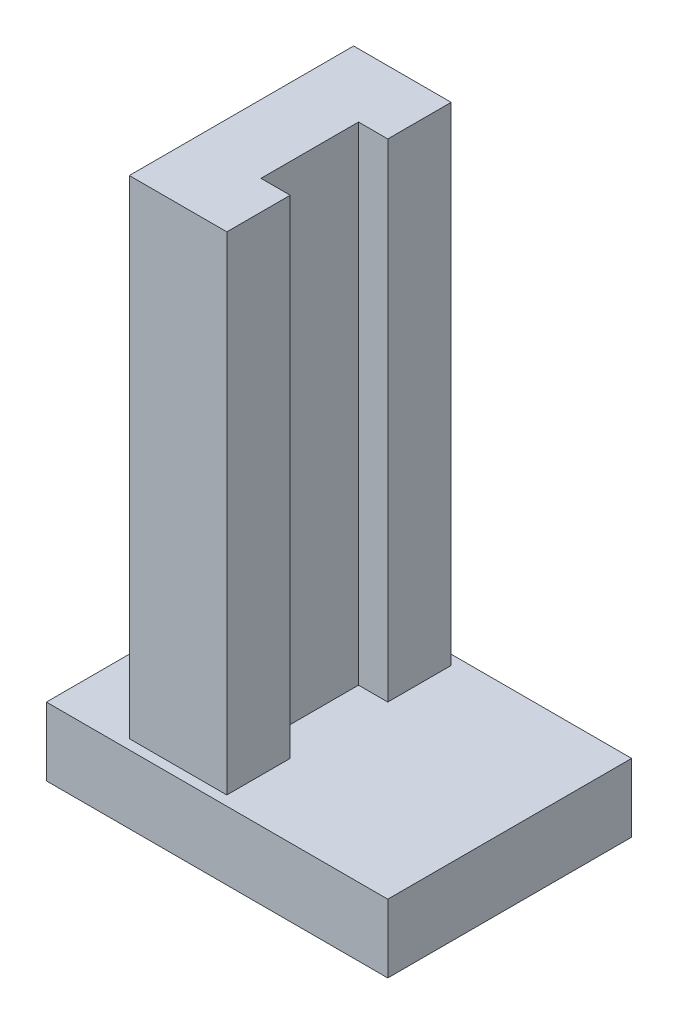
SolidWorks part; units mm, degrees
ref_plane "Alzado" through (0, 0, 0) normal (0, 0, 1) x (1, 0, 0)
ref_plane "Planta" through (0, 0, 0) normal (0, 1, 0) x (1, 0, 0)
ref_plane "Vista lateral" through (0, 0, 0) normal (1, 0, 0) x (0, 0, -1)
sketch "Croquis1" plane through (0, 0, 0) normal (0, 1, 0) x (1, 0, 0)
  line L1 (-87.5, -62.5) -> (87.5, -62.5)
  line L2 (-87.5, -62.5) -> (-87.5, 62.5)
  line L3 (-87.5, 62.5) -> (87.5, 62.5)
  line L4 (87.5, -62.5) -> (87.5, 62.5)
  line L5 (-87.5, -62.5) -> (87.5, 62.5) construction
  line L6 (-87.5, 62.5) -> (87.5, -62.5) construction
  point P0 (0, 0)
  dimension "D1" = 175
  dimension "D2" = 125
extrude "Saliente-Extruir1" add sketch "Croquis1" along normal blind 35
sketch "Croquis2" plane through (0, 35, 0) normal (0, 1, 0) x (1, 0, 0)
  line L0 (87.5, 62.5) -> (-87.5, 62.5) construction
  line L1 (0, -57.5) -> (-50, -57.5)
  line L2 (0, -57.5) -> (0, 57.5)
  line L3 (0, 57.5) -> (-50, 57.5)
  line L4 (-50, -57.5) -> (-50, 57.5)
  line L5 (0, -57.5) -> (-50, 57.5) construction
  line L6 (0, 57.5) -> (-50, -57.5) construction
  point P0 (-25, 0)
  dimension "D1" = 5
  dimension "D2" = 50
extrude "Saliente-Extruir2" add sketch "Croquis2" along normal blind 250
sketch "Croquis3" plane through (0, 0, 0) normal (1, 0, 0) x (0, 0, -1)
  line L0 (-57.5, 285) -> (57.5, 285) construction
  line L1 (-25, 35) -> (25, 35)
  line L2 (-25, 35) -> (-25, 285)
  line L3 (-25, 285) -> (25, 285)
  line L4 (25, 35) -> (25, 285)
  line L5 (-25, 35) -> (25, 285) construction
  line L6 (-25, 285) -> (25, 35) construction
  line L7 (-57.5, 35) -> (57.5, 35) construction
  point P0 (0, 160)
  dimension "D1" = 50
extrude "Cortar-Extruir1" cut sketch "Croquis3" against normal blind 15
